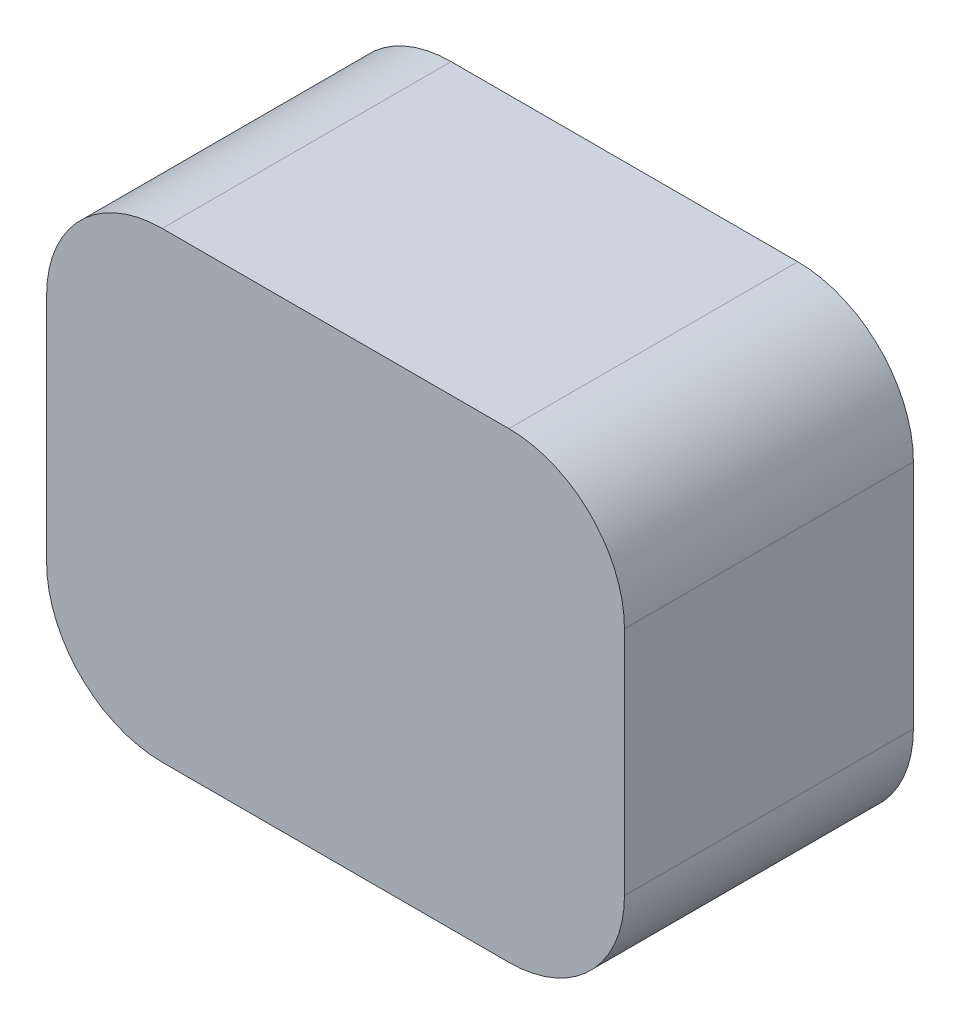
SolidWorks part; units mm, degrees
ref_plane "Alzado" through (0, 0, 0) normal (0, 0, 1) x (1, 0, 0)
ref_plane "Planta" through (0, 0, 0) normal (0, 1, 0) x (1, 0, 0)
ref_plane "Vista lateral" through (0, 0, 0) normal (1, 0, 0) x (0, 0, -1)
sketch "Croquis1" plane through (0, 0, 0) normal (0, 0, 1) x (1, 0, 0)
  line L1 (-23.3079, 36.7793) -> (-11.3079, 36.7793)
  line L2 (-27.3079, 32.7793) -> (-27.3079, 24.7793)
  line L3 (-23.3079, 20.7793) -> (-11.3079, 20.7793)
  line L4 (-7.3079, 32.7793) -> (-7.3079, 24.7793)
  line L5 (-27.3079, 36.7793) -> (-7.3079, 20.7793) construction
  line L6 (-27.3079, 20.7793) -> (-7.3079, 36.7793) construction
  arc A0 (-11.3079, 20.7793) -> (-7.3079, 24.7793) centre (-11.3079, 24.7793) ccw
  arc A1 (-23.3079, 20.7793) -> (-27.3079, 24.7793) centre (-23.3079, 24.7793) cw
  arc A2 (-11.3079, 36.7793) -> (-7.3079, 32.7793) centre (-11.3079, 32.7793) cw
  arc A3 (-23.3079, 36.7793) -> (-27.3079, 32.7793) centre (-23.3079, 32.7793) ccw
  point P0 (-17.3079, 28.7793)
  dimension "D3" = 4
  dimension "D1" = 20
  dimension "D2" = 16
extrude "Saliente-Extruir1" add sketch "Croquis1" along normal blind 10
